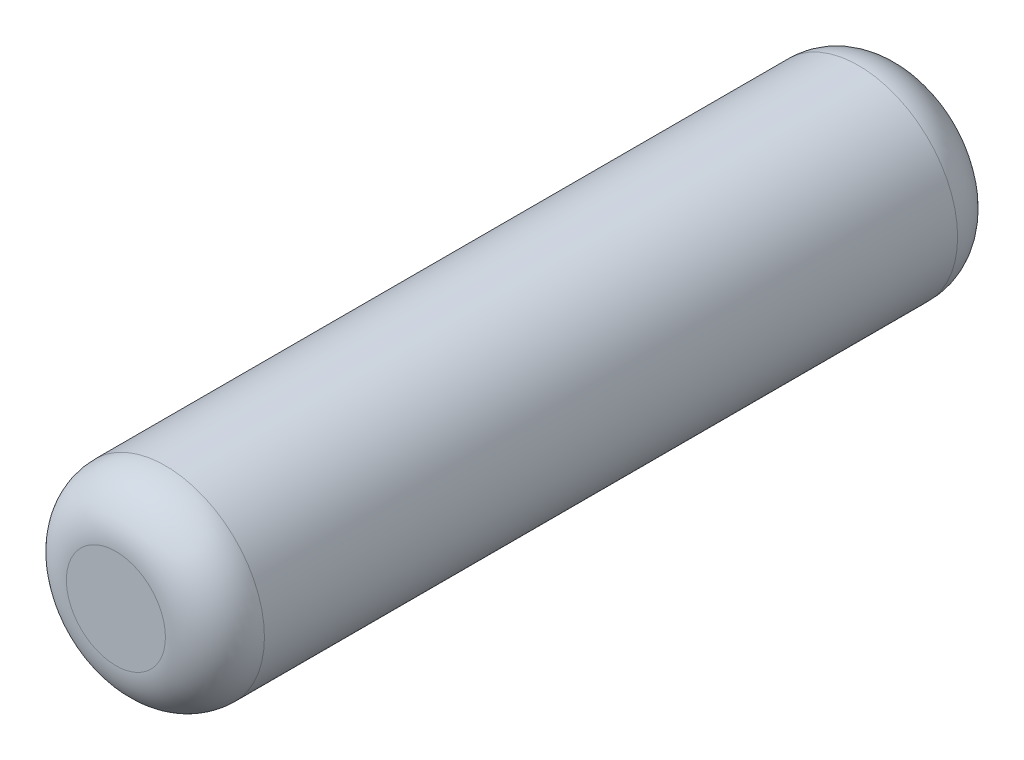
SolidWorks part; units mm, degrees
ref_plane "Front Plane" through (0, 0, 0) normal (0, 0, 1) x (1, 0, 0)
ref_plane "Top Plane" through (0, 0, 0) normal (0, 1, 0) x (1, 0, 0)
ref_plane "Right Plane" through (0, 0, 0) normal (1, 0, 0) x (0, 0, -1)
sketch "Sketch1" plane through (0, 0, 0) normal (0, 0, 1) x (1, 0, 0)
  circle A0 centre (0, 0) radius 50
  dimension "D1" = 100
extrude "Boss-Extrude1" add sketch "Sketch1" along normal mid plane 400
fillet "Fillet1" radius 25 2 edges at (50, 0, -200) (50, 0, 200)
